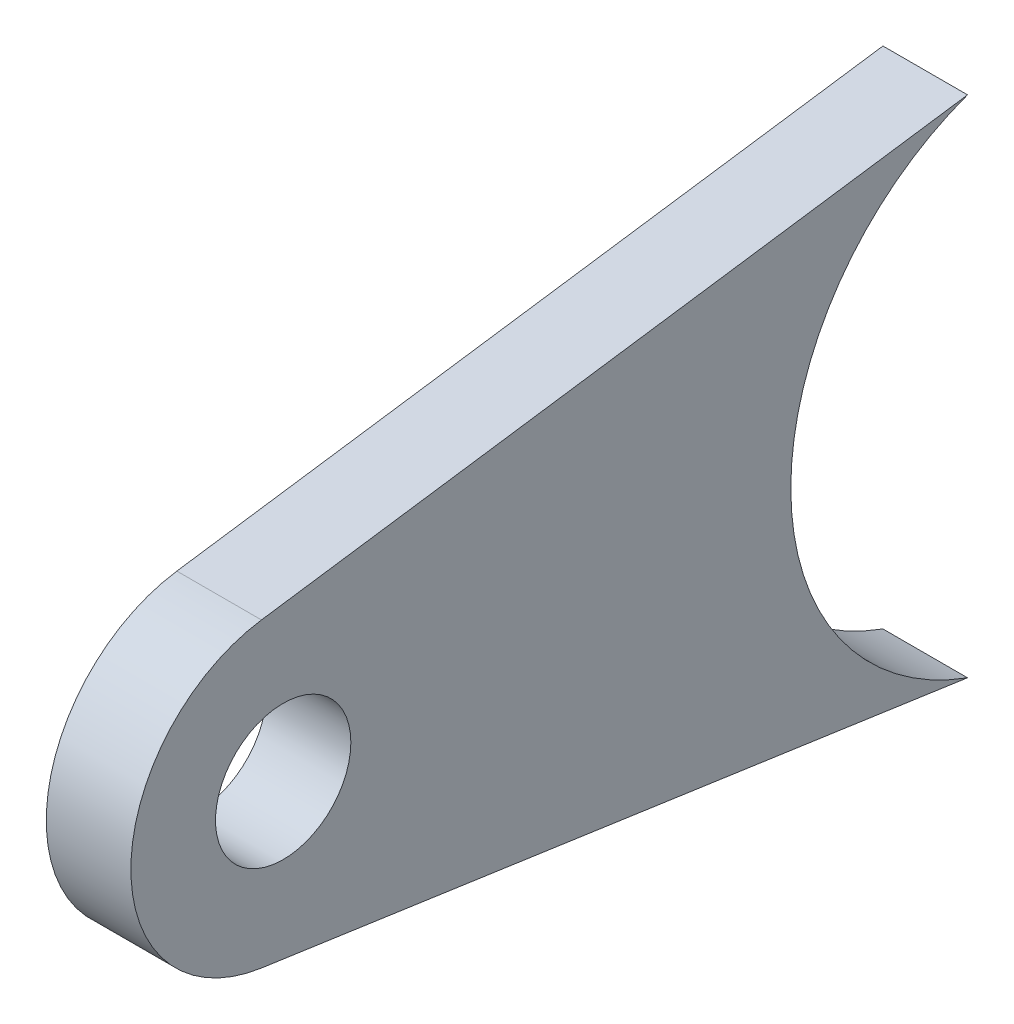
SolidWorks part; units mm, degrees
ref_plane "Front Plane" through (0, 0, 0) normal (1, 0, 0) x (0, 1, 0)
ref_plane "Top Plane" through (0, 0, 0) normal (0, 0, 1) x (0, 1, 0)
ref_plane "Right Plane" through (0, 0, 0) normal (0, 1, 0) x (-1, 0, 0)
sketch "Sketch1" plane through (0, 0, 0) normal (1, 0, 0) x (0, 1, 0)
  line L0 (0, 15.875) -> (0, 45.875)
  line L1 (0, 0) -> (50000, 0) construction
  line L2 (0, 0) -> (14.9176, 5.4296) construction
  line L3 (8.9081, 47.1579) -> (14.9176, 5.4296)
  line L4 (-8.9081, 47.1579) -> (-14.9176, 5.4296)
  circle A0 centre (0, 0) radius 15.875
  circle A1 centre (0, 45.875) radius 4
  arc A2 (8.9081, 47.1579) -> (-8.9081, 47.1579) centre (0, 45.875) ccw
  arc A3 (-8.9081, 47.1579) -> (0, 36.875) centre (0, 45.875) ccw construction
  circle A4 centre (0, 45.875) radius 9 construction
  arc A5 (0, 36.875) -> (8.9081, 47.1579) centre (0, 45.875) ccw construction
  dimension "D1" = 31.75
  dimension "D3" = 8
  dimension "D2" = 30
  dimension "D5" = 20
  dimension "D4" = 5
extrude "Boss-Extrude1" add sketch "Sketch1" along normal mid plane 5
